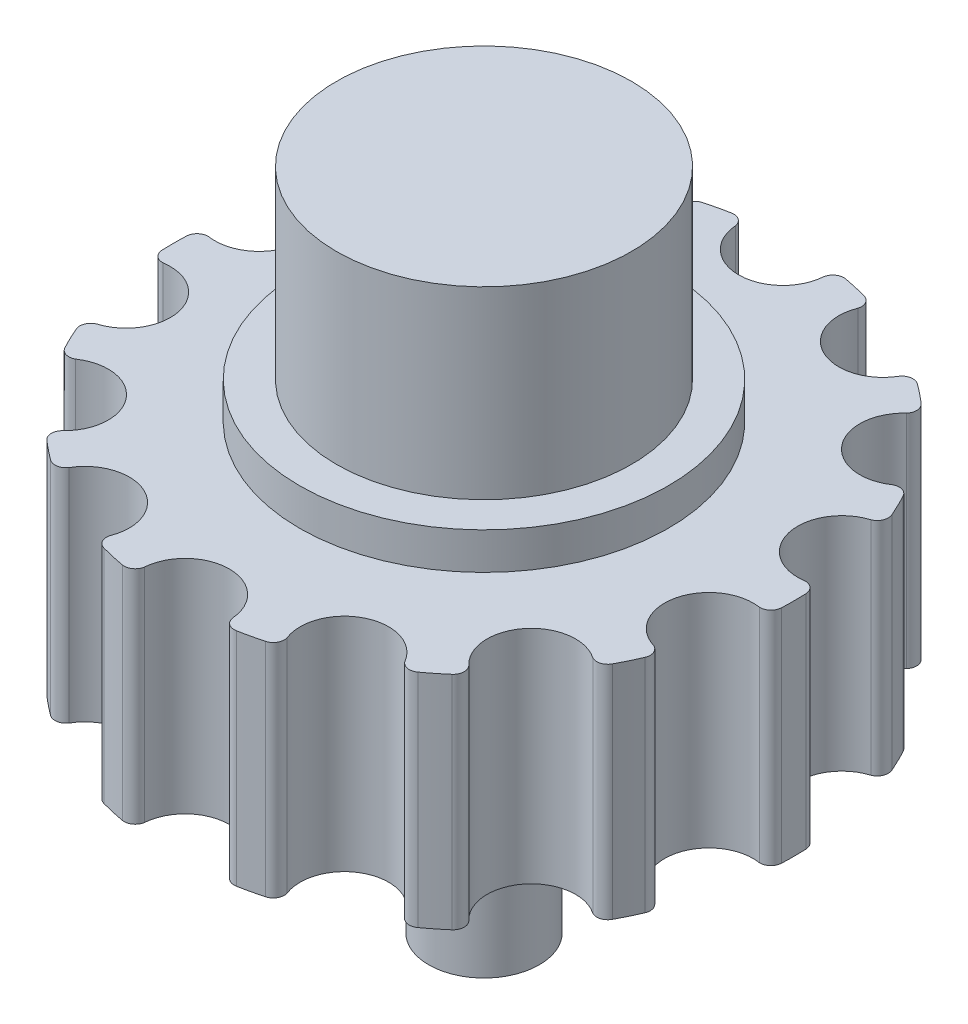
SolidWorks part; units mm, degrees
ref_plane "Front Plane" through (0, 0, 0) normal (0, 0, 1) x (1, 0, 0)
ref_plane "Top Plane" through (0, 0, 0) normal (0, 1, 0) x (1, 0, 0)
ref_plane "Right Plane" through (0, 0, 0) normal (1, 0, 0) x (0, 0, -1)
sketch "Sketch1" plane through (0, 0, 0) normal (0, 1, 0) x (1, 0, 0)
  line L0 (0, 0) -> (0, 4.4563) construction
  line L1 (0.5984, 4.0079) -> (0, 0) construction
  line L2 (1.1999, 3.8706) -> (0, 0) construction
  line L3 (0, 0) -> (-0.5984, 4.0079) construction
  circle A0 centre (0, 0) radius 4.4563 construction
  circle A2 centre (0, 0) radius 4.2023 construction
  circle A3 centre (0, 0) radius 3.4523 construction
  circle A4 centre (0, 0) radius 4.0523 construction
  arc A5 (0.5984, 4.0079) -> (0.7739, 4.1305) centre (0.7463, 3.983) cw
  arc A6 (0.7739, 4.1305) -> (1.0949, 4.0572) centre (0, 0) cw
  arc A7 (1.0949, 4.0572) -> (1.1999, 3.8706) centre (1.0558, 3.9124) cw
  arc A8 (0.5984, 4.0079) -> (-0.5984, 4.0079) centre (0, 4.0523) cw
  arc A9 (2.2781, 3.3514) -> (1.1999, 3.8706) centre (1.7582, 3.651) cw
  arc A10 (2.4894, 3.3856) -> (2.7468, 3.1804) centre (0, 0) cw
  arc A11 (2.2781, 3.3514) -> (2.4894, 3.3856) centre (2.4005, 3.2648) cw
  arc A12 (2.7468, 3.1804) -> (2.7605, 2.9667) centre (2.6488, 3.0668) cw
  arc A13 (3.5066, 2.0311) -> (2.7605, 2.9667) centre (3.1682, 2.5266) cw
  arc A14 (3.7118, 1.9702) -> (3.8547, 1.6736) centre (0, 0) cw
  arc A15 (3.5066, 2.0311) -> (3.7118, 1.9702) centre (3.5794, 1.8999) cw
  arc A16 (3.8547, 1.6736) -> (3.7743, 1.4752) centre (3.7171, 1.6139) cw
  arc A17 (4.0406, 0.3085) -> (3.7743, 1.4752) centre (3.9507, 0.9017) cw
  arc A18 (4.1991, 0.1646) -> (4.1991, -0.1646) centre (0, 0) cw
  arc A19 (4.0406, 0.3085) -> (4.1991, 0.1646) centre (4.0492, 0.1587) cw
  arc A20 (4.1991, -0.1646) -> (4.0406, -0.3085) centre (4.0492, -0.1587) cw
  arc A21 (3.7743, -1.4752) -> (4.0406, -0.3085) centre (3.9507, -0.9017) cw
  arc A22 (3.8547, -1.6736) -> (3.7118, -1.9702) centre (0, 0) cw
  arc A23 (3.7743, -1.4752) -> (3.8547, -1.6736) centre (3.7171, -1.6139) cw
  arc A24 (3.7118, -1.9702) -> (3.5066, -2.0311) centre (3.5794, -1.8999) cw
  arc A25 (2.7605, -2.9667) -> (3.5066, -2.0311) centre (3.1682, -2.5266) cw
  arc A26 (2.7468, -3.1804) -> (2.4894, -3.3856) centre (0, 0) cw
  arc A27 (2.7605, -2.9667) -> (2.7468, -3.1804) centre (2.6488, -3.0668) cw
  arc A28 (2.4894, -3.3856) -> (2.2781, -3.3514) centre (2.4005, -3.2648) cw
  arc A29 (1.1999, -3.8706) -> (2.2781, -3.3514) centre (1.7582, -3.651) cw
  arc A30 (1.0949, -4.0572) -> (0.7739, -4.1305) centre (0, 0) cw
  arc A31 (1.1999, -3.8706) -> (1.0949, -4.0572) centre (1.0558, -3.9124) cw
  arc A32 (0.7739, -4.1305) -> (0.5984, -4.0079) centre (0.7463, -3.983) cw
  arc A33 (-0.5984, -4.0079) -> (0.5984, -4.0079) centre (0, -4.0523) cw
  arc A34 (-0.7739, -4.1305) -> (-1.0949, -4.0572) centre (0, 0) cw
  arc A35 (-0.5984, -4.0079) -> (-0.7739, -4.1305) centre (-0.7463, -3.983) cw
  arc A36 (-1.0949, -4.0572) -> (-1.1999, -3.8706) centre (-1.0558, -3.9124) cw
  arc A37 (-2.2781, -3.3514) -> (-1.1999, -3.8706) centre (-1.7582, -3.651) cw
  arc A38 (-2.4894, -3.3856) -> (-2.7468, -3.1804) centre (0, 0) cw
  arc A39 (-2.2781, -3.3514) -> (-2.4894, -3.3856) centre (-2.4005, -3.2648) cw
  arc A40 (-2.7468, -3.1804) -> (-2.7605, -2.9667) centre (-2.6488, -3.0668) cw
  arc A41 (-3.5066, -2.0311) -> (-2.7605, -2.9667) centre (-3.1682, -2.5266) cw
  arc A42 (-3.7118, -1.9702) -> (-3.8547, -1.6736) centre (0, 0) cw
  arc A43 (-3.5066, -2.0311) -> (-3.7118, -1.9702) centre (-3.5794, -1.8999) cw
  arc A44 (-3.8547, -1.6736) -> (-3.7743, -1.4752) centre (-3.7171, -1.6139) cw
  arc A45 (-4.0406, -0.3085) -> (-3.7743, -1.4752) centre (-3.9507, -0.9017) cw
  arc A46 (-4.1991, -0.1646) -> (-4.1991, 0.1646) centre (0, 0) cw
  arc A47 (-4.0406, -0.3085) -> (-4.1991, -0.1646) centre (-4.0492, -0.1587) cw
  arc A48 (-4.1991, 0.1646) -> (-4.0406, 0.3085) centre (-4.0492, 0.1587) cw
  arc A49 (-3.7743, 1.4752) -> (-4.0406, 0.3085) centre (-3.9507, 0.9017) cw
  arc A50 (-3.8547, 1.6736) -> (-3.7118, 1.9702) centre (0, 0) cw
  arc A51 (-3.7743, 1.4752) -> (-3.8547, 1.6736) centre (-3.7171, 1.6139) cw
  arc A52 (-3.7118, 1.9702) -> (-3.5066, 2.0311) centre (-3.5794, 1.8999) cw
  arc A53 (-2.7605, 2.9667) -> (-3.5066, 2.0311) centre (-3.1682, 2.5266) cw
  arc A54 (-2.7468, 3.1804) -> (-2.4894, 3.3856) centre (0, 0) cw
  arc A55 (-2.7605, 2.9667) -> (-2.7468, 3.1804) centre (-2.6488, 3.0668) cw
  arc A56 (-2.4894, 3.3856) -> (-2.2781, 3.3514) centre (-2.4005, 3.2648) cw
  arc A57 (-1.1999, 3.8706) -> (-2.2781, 3.3514) centre (-1.7582, 3.651) cw
  arc A58 (-1.0949, 4.0572) -> (-0.7739, 4.1305) centre (0, 0) cw
  arc A59 (-1.1999, 3.8706) -> (-1.0949, 4.0572) centre (-1.0558, 3.9124) cw
  arc A60 (-0.7739, 4.1305) -> (-0.5984, 4.0079) centre (-0.7463, 3.983) cw
  point P122 (0, 0)
  dimension "D1" = 0.75
  dimension "D2" = 0.254
  dimension "D3" = 25.714
  dimension "D4" = 0.6
  dimension "D6" = 8.9127
  dimension "D5" = 14
extrude "Boss-Extrude1" add sketch "Sketch1" along normal blind 3 contours A60 A58 A59 A57 A56 A54 A55 A53 A52 A50 A51 A49 A48 A46 A47 A45 A44 A42 A43 A41 A40 A38 A39 A37 A36 A34 A35 A33 A32 A30 A31 A29 A28 A26 A27 A25 A24 A22 A23 A21 A20 A18 A19 A17 A16 A14 A15 A13 A12 A10 A11
sketch "Sketch2" plane through (0, 0, 0) normal (0, -1, 0) x (-1, 0, 0)
  circle A0 centre (0, 0) radius 0.75
  dimension "D1" = 1.5
extrude "Boss-Extrude2" add sketch "Sketch2" along normal blind 3
sketch "Sketch3" plane through (0, 3, 0) normal (0, 1, 0) x (1, 0, 0)
  circle A0 centre (0, 0) radius 2.5
  dimension "D1" = 5
extrude "Boss-Extrude3" add sketch "Sketch3" along normal blind 0.5
sketch "Sketch4" plane through (0, 3.5, 0) normal (0, 1, 0) x (1, 0, 0)
  circle A0 centre (0, 0) radius 2
  dimension "D1" = 4
extrude "Boss-Extrude4" add sketch "Sketch4" along normal blind 2.5
